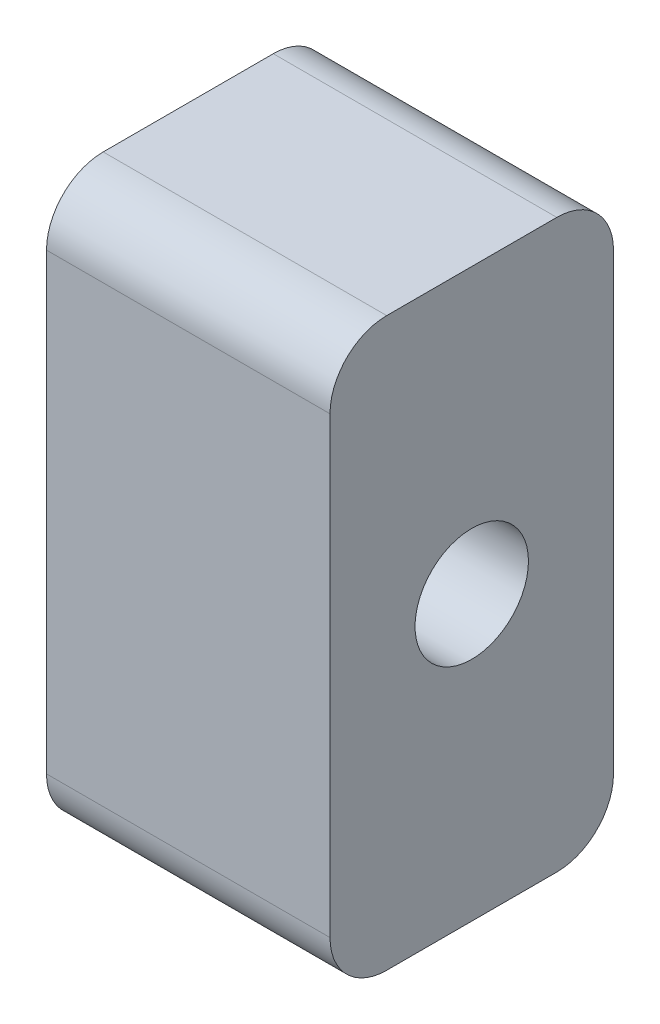
SolidWorks part; units mm, degrees
ref_plane "Alzado" through (0, 0, 0) normal (1, 0, 0) x (0, 1, 0)
ref_plane "Planta" through (0, 0, 0) normal (0, 0, 1) x (0, 1, 0)
ref_plane "Vista lateral" through (0, 0, 0) normal (0, 1, 0) x (-1, 0, 0)
sketch "Croquis2" plane through (0, 0, 0) normal (1, 0, 0) x (0, 1, 0)
  line L1 (-101.6, 63.5) -> (101.6, 63.5)
  line L2 (-127, 38.1) -> (-127, -38.1)
  line L3 (-101.6, -63.5) -> (101.6, -63.5)
  line L4 (127, 38.1) -> (127, -38.1)
  line L5 (-127, 63.5) -> (127, -63.5) construction
  line L6 (-127, -63.5) -> (127, 63.5) construction
  circle A0 centre (0, 0) radius 25.4
  arc A1 (101.6, 63.5) -> (127, 38.1) centre (101.6, 38.1) cw
  arc A2 (101.6, -63.5) -> (127, -38.1) centre (101.6, -38.1) ccw
  arc A3 (-127, -38.1) -> (-101.6, -63.5) centre (-101.6, -38.1) ccw
  arc A4 (-101.6, 63.5) -> (-127, 38.1) centre (-101.6, 38.1) ccw
  point P0 (0, 0)
  dimension "D3" = 25.4
  dimension "D1" = 254
  dimension "D2" = 127
extrude "Saliente-Extruir1" add sketch "Croquis2" along normal blind 127
